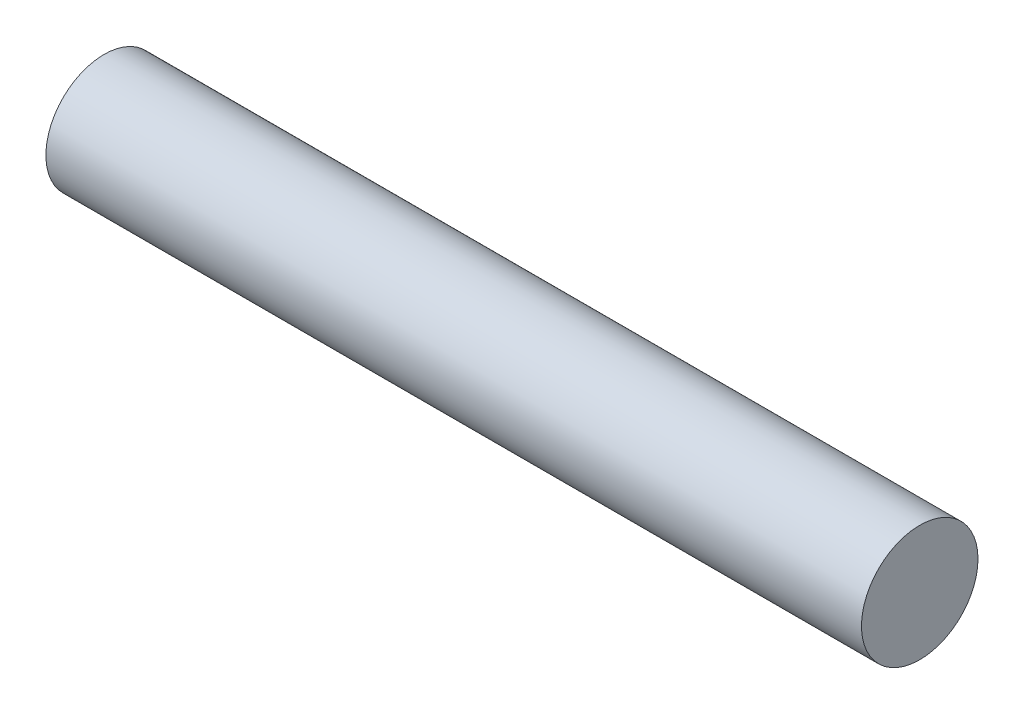
SolidWorks part; units mm, degrees
ref_plane "Front Plane" through (0, 0, 0) normal (0, 0, 1) x (1, 0, 0)
ref_plane "Top Plane" through (0, 0, 0) normal (0, 1, 0) x (1, 0, 0)
ref_plane "Right Plane" through (0, 0, 0) normal (1, 0, 0) x (0, 0, -1)
sketch "Sketch1" plane through (0, 0, 0) normal (1, 0, 0) x (0, 0, -1)
  circle A0 centre (0, 0) radius 1
  dimension "D1" = 2
extrude "Boss-Extrude1" add sketch "Sketch1" along normal blind 14
ref_plane "Plane2" through (7, 0, 0) normal (1, 0, 0) x (0, 0, -1)
